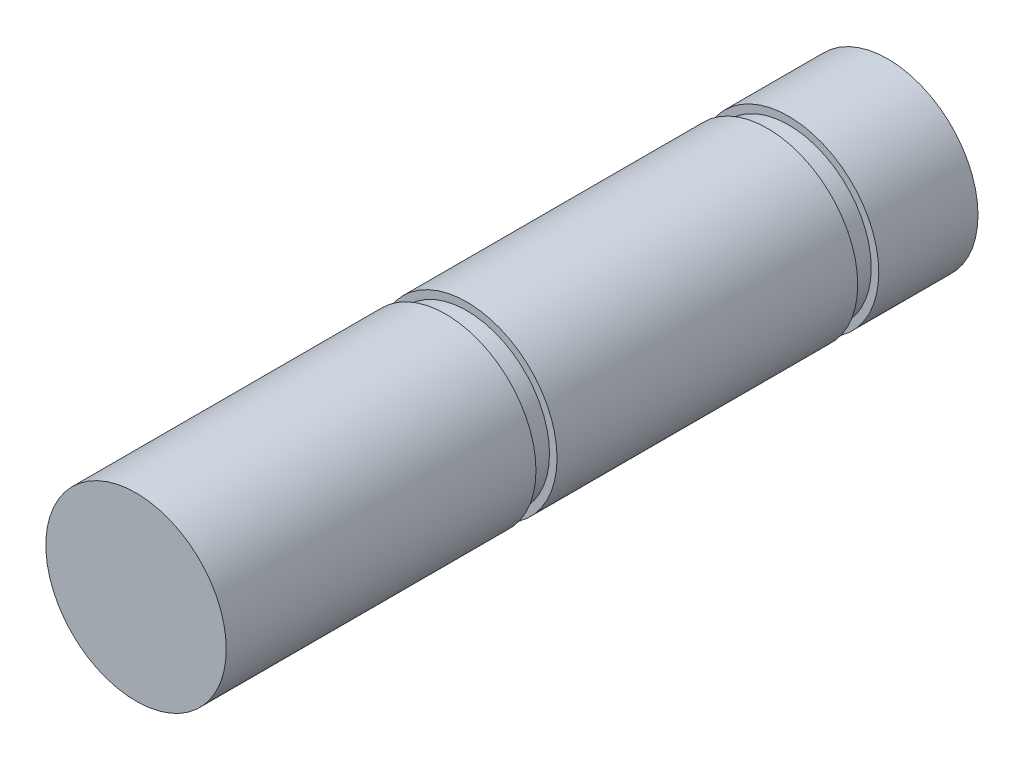
SolidWorks part; units mm, degrees
ref_plane "정면" through (0, 0, 0) normal (0, 0, 1) x (1, 0, 0)
ref_plane "윗면" through (0, 0, 0) normal (0, 1, 0) x (1, 0, 0)
ref_plane "우측면" through (0, 0, 0) normal (1, 0, 0) x (0, 0, -1)
sketch "스케치1" plane through (0, 0, 0) normal (0, 0, 1) x (1, 0, 0)
  circle A0 centre (0, 0) radius 3
  dimension "D1" = 6
extrude "보스-돌출1" add sketch "스케치1" along normal blind 25
ref_plane "평면1" through (0, 0, 3.65) normal (0, 0, 1) x (1, 0, 0)
sketch "스케치2" plane through (0, 0, 3.65) normal (0, 0, 1) x (1, 0, 0)
  circle A0 centre (0, 0) radius 2.75
  circle A1 centre (0, 0) radius 3
  circle A2 centre (0, 0) radius 3
  dimension "D1" = 0
  dimension "D2" = 0.25
extrude "컷-돌출1" cut sketch "스케치2" against normal blind 0.35 and the other way blind 0.35
ref_plane "평면2" through (0, 0, 14.7) normal (0, 0, 1) x (1, 0, 0)
sketch "스케치3" plane through (0, 0, 14.7) normal (0, 0, 1) x (1, 0, 0)
  circle A0 centre (0, 0) radius 2.75
  circle A1 centre (0, 0) radius 3
  circle A2 centre (0, 0) radius 3
  dimension "D1" = 0
  dimension "D2" = 0.25
extrude "컷-돌출2" cut sketch "스케치3" against normal blind 0.7 contours A2 A0
